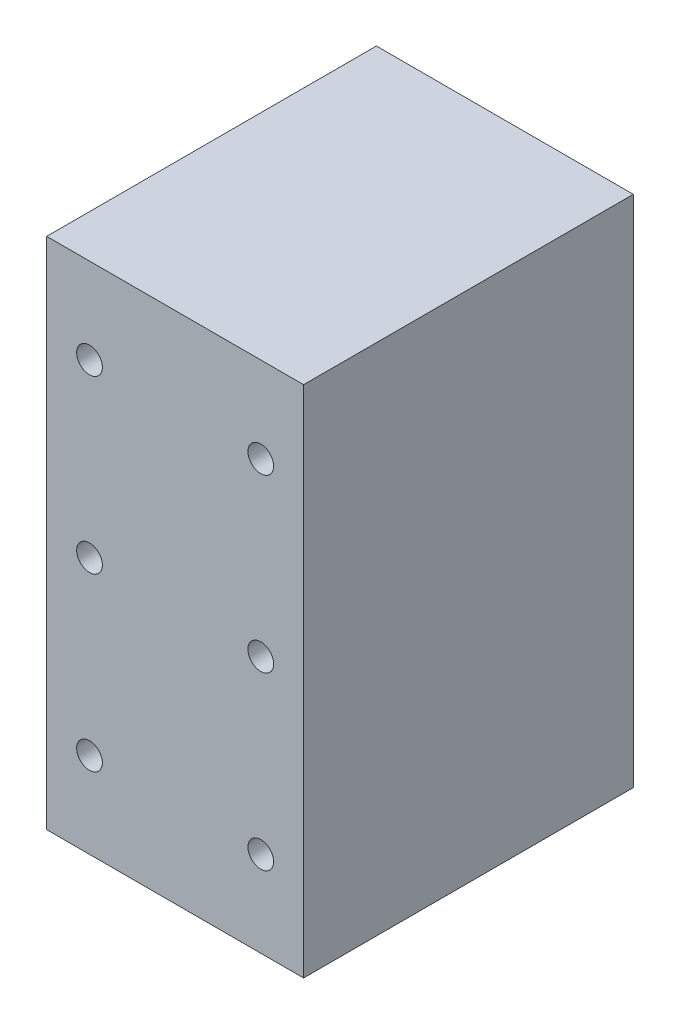
SolidWorks part; units mm, degrees
ref_plane "Plan de face" through (0, 0, 0) normal (0, 0, 1) x (1, 0, 0)
ref_plane "Plan de dessus" through (0, 0, 0) normal (0, 1, 0) x (1, 0, 0)
ref_plane "Plan de droite" through (0, 0, 0) normal (1, 0, 0) x (0, 0, -1)
sketch "Esquisse1" plane through (0, 0, 0) normal (0, 0, 1) x (1, 0, 0)
  line L1 (15, -30) -> (-15, -30)
  line L2 (15, -30) -> (15, 30)
  line L3 (15, 30) -> (-15, 30)
  line L4 (-15, -30) -> (-15, 30)
  line L5 (15, -30) -> (-15, 30) construction
  line L6 (15, 30) -> (-15, -30) construction
  point P0 (0, 0)
  dimension "D1" = 60
  dimension "D2" = 30
extrude "Extrusion1" add sketch "Esquisse1" along normal blind 38.5
sketch "Esquisse2" plane through (0, 0, 38.5) normal (0, 0, 1) x (1, 0, 0)
  line L0 (-15, 30) -> (-15, -30) construction
  line L1 (15, 30) -> (-15, 30) construction
  circle A0 centre (-10, 20) radius 1.5
  point P6 (-25.5226, 25.3166)
  dimension "D1" = 3
  dimension "D2" = 5
  dimension "D3" = 10
extrude "Extrusion2" cut sketch "Esquisse2" against normal through all
pattern_linear "Répétition linéaire1" count 3 spacing 20 along (0, -1, 0) count 2 spacing 20 along (1, 0, 0) of "Extrusion2"
